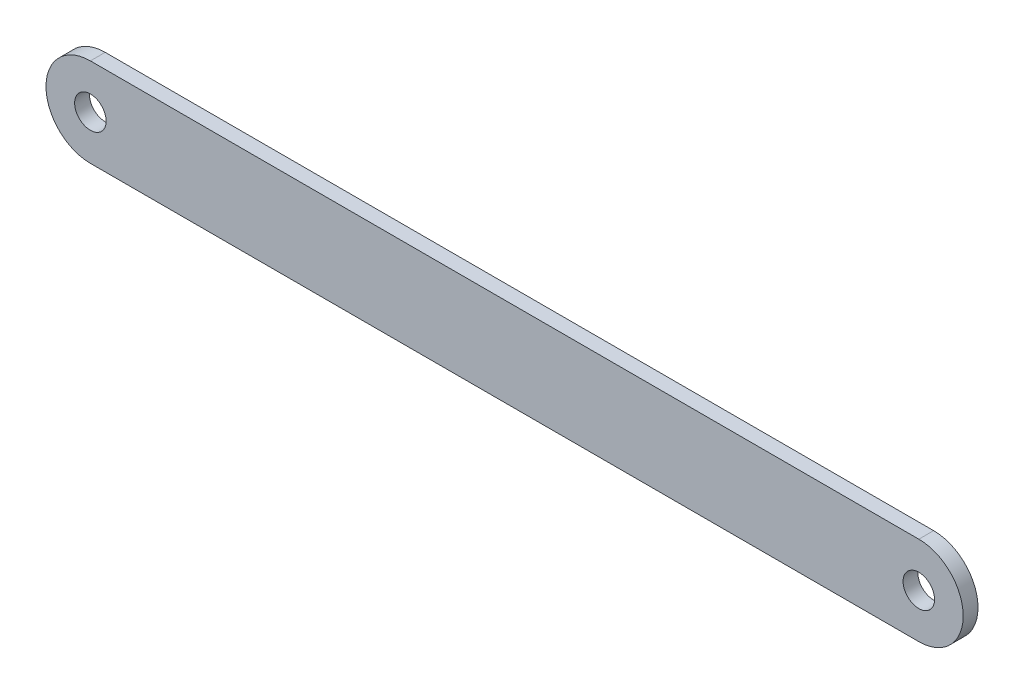
SolidWorks part; units mm, degrees
material "6063-O"
ref_plane "Front Plane" through (0, 0, 0) normal (0, 0, 1) x (1, 0, 0)
ref_plane "Top Plane" through (0, 0, 0) normal (0, 1, 0) x (1, 0, 0)
ref_plane "Right Plane" through (0, 0, 0) normal (1, 0, 0) x (0, 0, -1)
sketch "Sketch2" plane through (0, 0, 0) normal (0, 0, 1) x (1, 0, 0)
  line L0 (88.9, 0) -> (-88.9, 0) construction
  line L1 (1.7463, 0) -> (-1.7463, 0) construction
  line L2 (88.9, -9.525) -> (-88.9, -9.525)
  line L3 (88.9, 9.525) -> (-88.9, 9.525)
  arc A0 (88.9, -9.525) -> (88.9, 9.525) centre (88.9, 0) ccw
  arc A1 (-88.9, 9.525) -> (-88.9, -9.525) centre (-88.9, 0) ccw
  point P5 (0, 0)
  dimension "D1" = 19.05
  dimension "D2" = 196.85
extrude "Boss-Extrude1" add sketch "Sketch2" along normal mid plane 3.175
hole_wizard "1/4 Clearance Hole1" positions "Sketch4" profile "Sketch5" hole size "1/4" standard "ANSI Inch" end condition through all
sketch "Sketch4" plane through (0, 0, 1.5875) normal (0, 0, 1) x (1, 0, 0)
  point P0 (-88.9, 0)
  point P3 (88.9, 0)
sketch "Sketch5" plane through (-88.9, 0, 1.5875) normal (1, 0, 0) x (0, -1, 0)
  line L0 (0, 0) -> (0, 3.175)
  line L1 (0, 3.175) -> (3.3782, 3.175)
  line L2 (3.3782, 3.175) -> (3.3782, 0)
  line L5 (3.3782, 0) -> (0, 0)
  line L11 (0, -6.35) -> (0, 107.95) construction
  dimension "Thru Hole Dia." = 6.7564
  dimension "Thru Hole Depth" = 3.175
